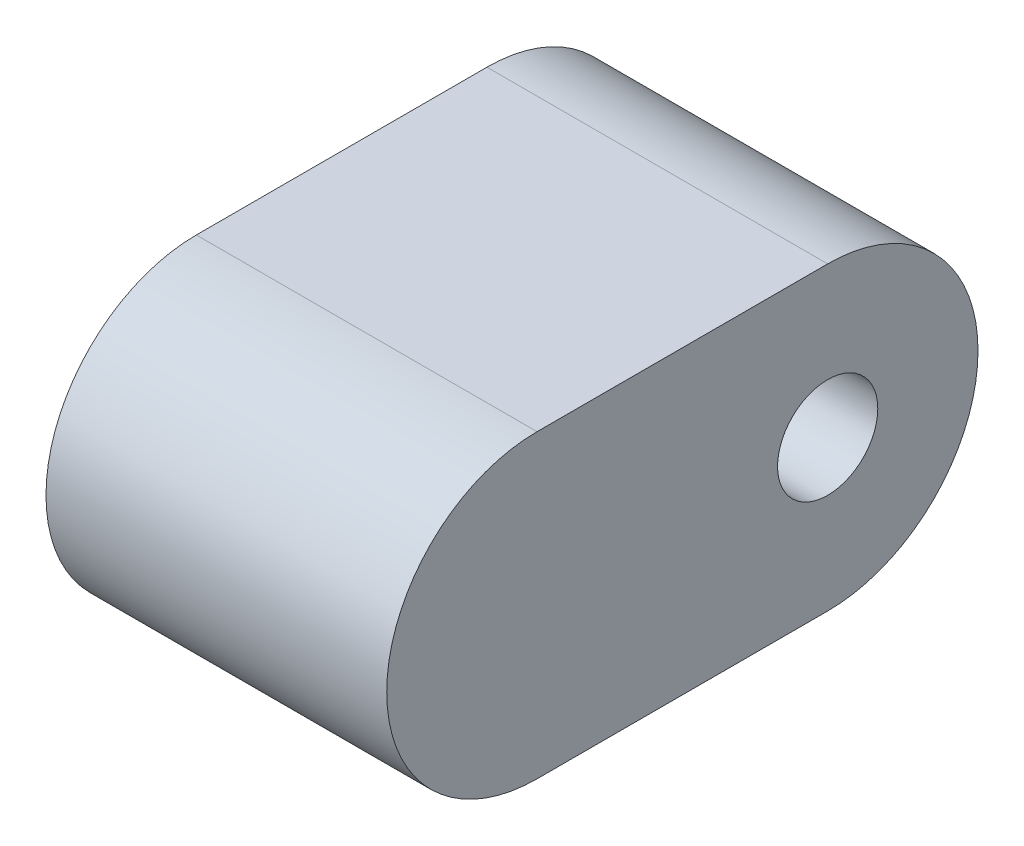
SolidWorks part; units mm, degrees
ref_plane "Alzado" through (0, 0, 0) normal (0, 0, 1) x (1, 0, 0)
ref_plane "Planta" through (0, 0, 0) normal (0, 1, 0) x (1, 0, 0)
ref_plane "Vista lateral" through (0, 0, 0) normal (1, 0, 0) x (0, 0, -1)
sketch "Croquis1" plane through (0, 0, 0) normal (1, 0, 0) x (0, 0, -1)
  line L0 (0, 7.5) -> (-14.5, 7.5)
  line L1 (0, -7.5) -> (-14.5, -7.5)
  circle A0 centre (0, 0) radius 2.5
  arc A1 (0, -7.5) -> (0, 7.5) centre (0, 0) ccw
  arc A2 (-14.5, 7.5) -> (-14.5, -7.5) centre (-14.5, 0) ccw
  dimension "D2" = 15
  dimension "D1" = 14.5
  dimension "D3" = 5
extrude "Saliente-Extruir1" add sketch "Croquis1" along normal mid plane 17
sketch "Croquis2" plane through (0, 0, 0) normal (0, 1, 0) x (1, 0, 0)
  line L0 (8.5, 7.5) -> (-8.5, 7.5) construction
  line L1 (2.8333, 7.5) -> (-2.8333, 7.5)
  line L2 (2.8333, 7.5) -> (2.8333, -7.25)
  line L3 (2.8333, -7.25) -> (-2.8333, -7.25)
  line L4 (-2.8333, 7.5) -> (-2.8333, -7.25)
  line L5 (8.5, 0) -> (8.5, -14.5) construction
  point P6 (0, 7.5)
  point P10 (8.5, -7.25)
  dimension "D1" = 5.6667
